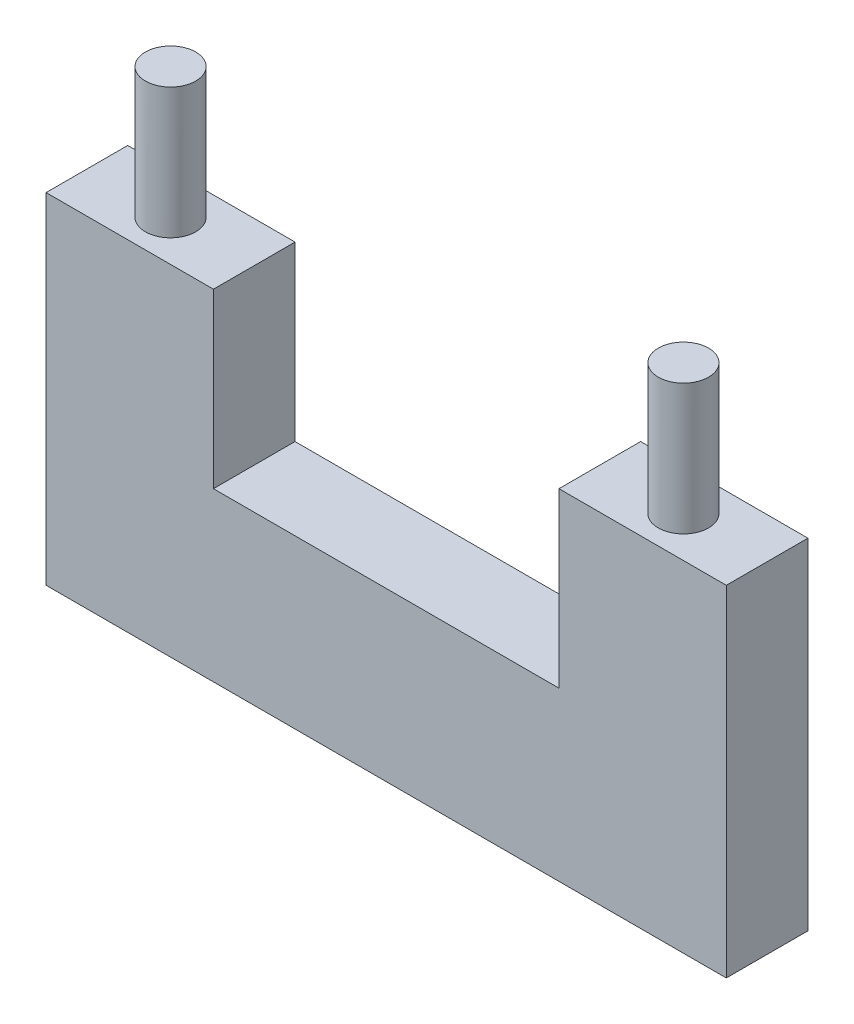
SolidWorks part; units mm, degrees
ref_plane "Front Plane" through (0, 0, 0) normal (0, 0, 1) x (1, 0, 0)
ref_plane "Top Plane" through (0, 0, 0) normal (0, 1, 0) x (1, 0, 0)
ref_plane "Right Plane" through (0, 0, 0) normal (1, 0, 0) x (0, 0, -1)
sketch "Sketch1" plane through (0, 0, 0) normal (0, 0, 1) x (1, 0, 0)
  line L1 (-12.5, 6.25) -> (12.5, 6.25)
  line L2 (-12.5, 6.25) -> (-12.5, -6.25)
  line L3 (-12.5, -6.25) -> (12.5, -6.25)
  line L4 (12.5, 6.25) -> (12.5, -6.25)
  line L5 (-12.5, 6.25) -> (12.5, -6.25) construction
  line L6 (-12.5, -6.25) -> (12.5, 6.25) construction
  point P0 (0, 0)
  dimension "D1" = 25
  dimension "D2" = 12.5
extrude "Boss-Extrude1" add sketch "Sketch1" along normal blind 3
sketch "Sketch2" plane through (0, 0, 3) normal (0, 0, 1) x (1, 0, 0)
  line L0 (12.5, 6.25) -> (-12.5, 6.25) construction
  line L1 (-6.35, 6.25) -> (6.35, 6.25)
  line L2 (-6.35, 6.25) -> (-6.35, -0.1)
  line L3 (-6.35, -0.1) -> (6.35, -0.1)
  line L4 (6.35, 6.25) -> (6.35, -0.1)
  line L5 (-12.5, -6.25) -> (12.5, -6.25) construction
  dimension "D1" = 6.15
  dimension "D2" = 6.15
  dimension "D3" = 6.15
extrude "Cut-Extrude1" cut sketch "Sketch2" against normal blind 3
sketch "Sketch3" plane through (0, 6.25, 0) normal (0, 1, 0) x (1, 0, 0)
  line L0 (-6.35, 0) -> (-12.5, 0) construction
  line L1 (12.5, 0) -> (6.35, 0) construction
  line L2 (-12.5, -3) -> (-12.5, 0) construction
  line L3 (12.5, -3) -> (12.5, 0) construction
  circle A0 centre (-9.425, -1.5) radius 0.925
  circle A1 centre (9.425, -1.5) radius 0.925
  dimension "D1" = 1.85
  dimension "D3" = 1.85
  dimension "D2" = 1.5
  dimension "D4" = 1.5
  dimension "D5" = 3.075
  dimension "D6" = 3.075
extrude "Boss-Extrude2" add sketch "Sketch3" along normal blind 4.8
